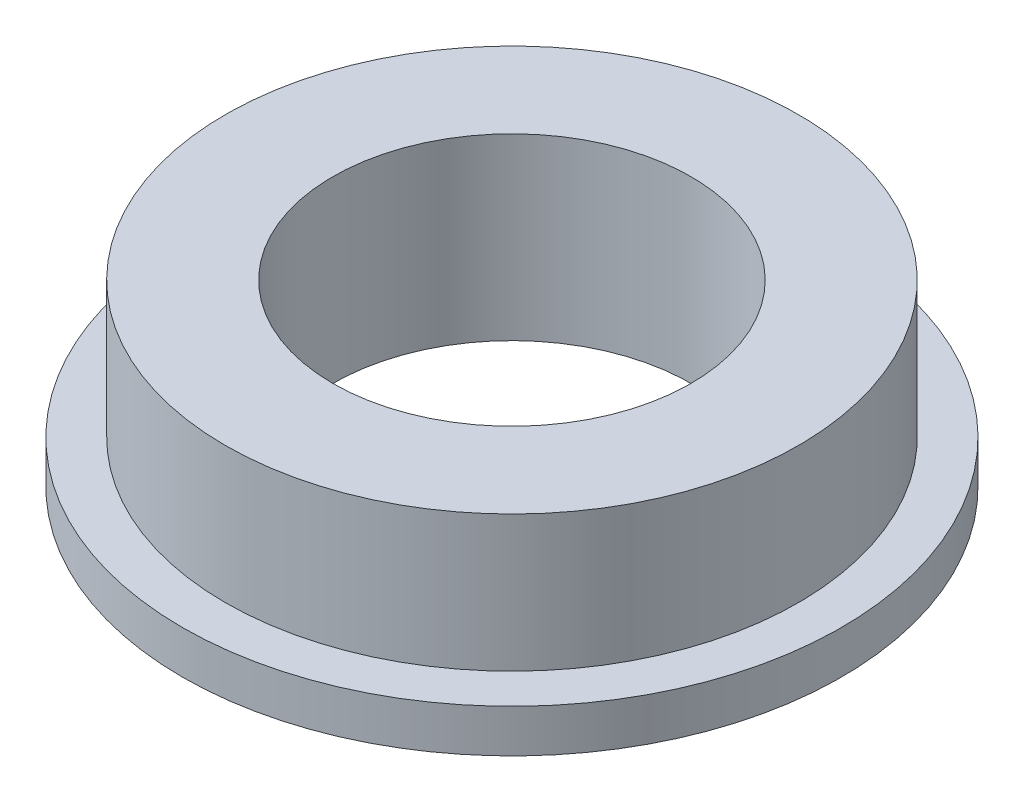
SolidWorks part; units mm, degrees
ref_plane "前视基准面" through (0, 0, 0) normal (0, 0, 1) x (1, 0, 0)
ref_plane "上视基准面" through (0, 0, 0) normal (0, 1, 0) x (1, 0, 0)
ref_plane "右视基准面" through (0, 0, 0) normal (1, 0, 0) x (0, 0, -1)
other "Configuration Table"
sketch "草图1" plane through (0, 0, 0) normal (0, 1, 0) x (1, 0, 0)
  circle A0 centre (0, 0) radius 4
  circle A1 centre (0, 0) radius 2.5
  dimension "D1" = 8
  dimension "D2" = 5
extrude "凸台-拉伸1" add sketch "草图1" along normal blind 2.5
sketch "草图2" plane through (0, 0, 0) normal (0, 1, 0) x (1, 0, 0)
  circle A0 centre (0, 0) radius 4.6
  circle A1 centre (0, 0) radius 4
  dimension "D1" = 8
  dimension "D2" = 9.2
extrude "凸台-拉伸2" add sketch "草图2" along normal blind 0.6
